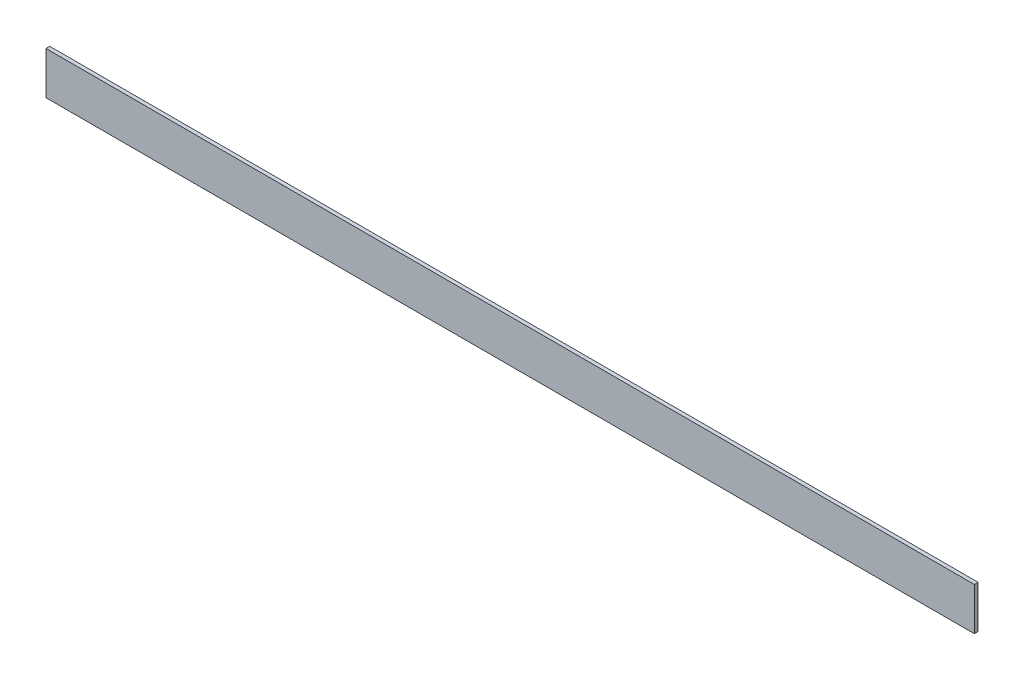
SolidWorks part; units mm, degrees
ref_plane "Front Plane" through (0, 0, 0) normal (0, 0, 1) x (1, 0, 0)
ref_plane "Top Plane" through (0, 0, 0) normal (0, 1, 0) x (1, 0, 0)
ref_plane "Right Plane" through (0, 0, 0) normal (1, 0, 0) x (0, 0, -1)
sketch "Sketch1" plane through (0, 0, 0) normal (0, 0, 1) x (1, 0, 0)
  line L0 (2500, 115) -> (2500, 0)
  line L1 (2500, 115) -> (0, 115)
  line L2 (2500, 0) -> (0, 0)
  line L3 (0, 115) -> (0, 0)
  point P0 (0, 0)
other "Pen Sketch1" parameters "D1"=69.7562, "D2"=44.2015
extrude "Boss-Extrude1" add sketch "Sketch1" along normal blind 10
